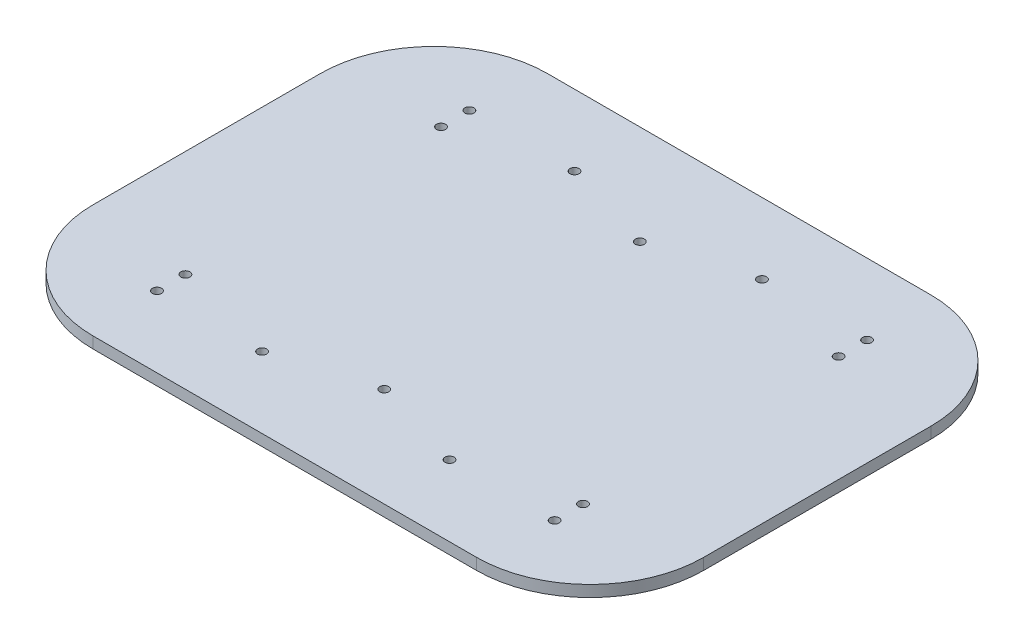
SolidWorks part; units mm, degrees
ref_plane "Front Plane" through (0, 0, 0) normal (0, 0, 1) x (1, 0, 0)
ref_plane "Top Plane" through (0, 0, 0) normal (0, 1, 0) x (1, 0, 0)
ref_plane "Right Plane" through (0, 0, 0) normal (1, 0, 0) x (0, 0, -1)
sketch "Sketch1" plane through (0, 0, 0) normal (0, 1, 0) x (1, 0, 0)
  line L1 (-107.5, 80) -> (107.5, 80)
  line L2 (-107.5, 80) -> (-107.5, -80)
  line L3 (-107.5, -80) -> (107.5, -80)
  line L4 (107.5, 80) -> (107.5, -80)
  line L5 (-107.5, 80) -> (107.5, -80) construction
  line L6 (-107.5, -80) -> (107.5, 80) construction
  point P0 (0, 0)
  dimension "D1" = 160
  dimension "D2" = 215
extrude "Boss-Extrude1" add sketch "Sketch1" along normal blind 4 contours L2 L1 L4 L3
sketch "Sketch3" plane through (0, 0, 0) normal (0, -1, 0) x (1, 0, 0)
  line L0 (-107.5, -80) -> (-107.5, 80) construction
  line L1 (-107.5, 80) -> (107.5, 80) construction
  line L2 (107.5, -80) -> (107.5, 80) construction
  line L6 (-107.5, 0) -> (107.5, 0) construction
  line L7 (0, 80) -> (0, -80) construction
  line L8 (-107.5, -80) -> (107.5, -80) construction
  circle A0 centre (-70, 55) radius 10.2331
  circle A4 centre (33, 55) radius 10.2331
  circle A5 centre (-33, 55) radius 10.2331
  circle A6 centre (70, 55) radius 10.2331
  circle A7 centre (70, -55) radius 10.2331
  circle A8 centre (33, -55) radius 10.2331
  circle A9 centre (-33, -55) radius 10.2331
  circle A10 centre (-70, -55) radius 10.2331
  point P0 (-70, 55)
  point P6 (33, 55)
  point P12 (-33, 55)
  point P14 (70, 55)
  point P16 (70, -55)
  point P22 (33, -55)
  point P24 (-33, -55)
  point P26 (-70, -55)
  dimension "D1" = 55
  dimension "D3" = 33
  dimension "D5" = 55
  dimension "D7" = 70
  dimension "D2" = 70
  dimension "D4" = 55
  dimension "D6" = 33
hole_wizard "Ø1.0 (3.2) Diameter Hole1" positions "Sketch3" profile "Sketch6" hole size "Ø1.0" standard "ANSI Metric" end condition through all
sketch "Sketch6" plane through (-70, 0, 55) normal (1, 0, 0) x (0, 0, -1)
  line L0 (0, 0) -> (0, 4)
  line L1 (0, 4) -> (1.6, 4)
  line L2 (1.6, 4) -> (1.6, 0)
  line L5 (1.6, 0) -> (0, 0)
  line L11 (0, -6.35) -> (0, 107.95) construction
  dimension "Thru Hole Dia." = 3.2
  dimension "Thru Hole Depth" = 4
fillet "Fillet1" radius 40 2 edges at (-107.5, 2, -80) (-107.5, 2, 80)
fillet "Fillet2" radius 40 2 edges at (107.5, 2, -80) (107.5, 2, 80)
sketch "Sketch8" plane through (0, 0, 0) normal (0, -1, 0) x (1, 0, 0)
  line L0 (-107.5, -40) -> (-107.5, 40) construction
  line L1 (-67.5, -80) -> (67.5, -80) construction
  line L3 (2.2, 0) -> (-2.2, 0) construction
  circle A0 centre (-70, -45) radius 1.6
  circle A1 centre (0, -45) radius 1.6
  circle A2 centre (70, -45) radius 1.6
  circle A3 centre (70, 45) radius 1.6
  circle A4 centre (0, 45) radius 1.6
  circle A5 centre (-70, 45) radius 1.6
  dimension "D1" = 37.5
  dimension "D7" = 3.2
  dimension "D2" = 35
  dimension "D3" = 35
  dimension "D4" = 107.5
  dimension "D5" = 177.5
  dimension "D6" = 35
extrude "Cut-Extrude1" cut sketch "Sketch8" against normal through all
